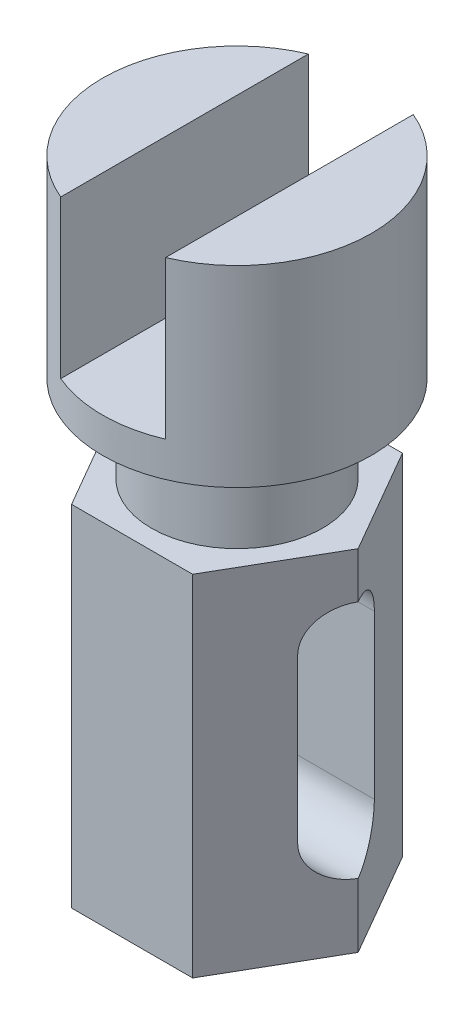
SolidWorks part; units mm, degrees
ref_plane "Front Plane" through (0, 0, 0) normal (0, 0, 1) x (1, 0, 0)
ref_plane "Top Plane" through (0, 0, 0) normal (0, 1, 0) x (1, 0, 0)
ref_plane "Right Plane" through (0, 0, 0) normal (1, 0, 0) x (0, 0, -1)
sketch "Sketch4" plane through (0, 0, 0) normal (0, 1, 0) x (1, 0, 0)
  line L1 (34.641, 0) -> (17.3205, 30)
  line L2 (17.3205, 30) -> (-17.3205, 30)
  line L3 (-17.3205, 30) -> (-34.641, 0)
  line L4 (-34.641, 0) -> (-17.3205, -30)
  line L5 (-17.3205, -30) -> (17.3205, -30)
  line L6 (17.3205, -30) -> (34.641, 0)
  circle A0 centre (0, 0) radius 30 construction
  point P1 (30, 0)
  point P10 (30, 0)
  dimension "D1" = 60
extrude "Boss-Extrude1" add sketch "Sketch4" along normal blind 100
sketch "Sketch5" plane through (0, 100, 0) normal (0, 1, 0) x (1, 0, 0)
  circle A0 centre (0, 0) radius 24.5
extrude "Boss-Extrude3" add sketch "Sketch5" along normal blind 25
ref_plane "Plane1" through (0, 125, 0) normal (0, 1, 0) x (1, 0, 0)
sketch "Sketch7" plane through (0, 125, 0) normal (0, 1, 0) x (1, 0, 0)
  circle A0 centre (0, 0) radius 38.4617
extrude "Boss-Extrude4" add sketch "Sketch7" along normal blind 55
sketch "Sketch8" plane through (0, 180, 0) normal (0, 1, 0) x (1, 0, 0)
  line L1 (-15, -39.4745) -> (15, -39.4745)
  line L2 (-15, -39.4745) -> (-15, 39.4745)
  line L3 (-15, 39.4745) -> (15, 39.4745)
  line L4 (15, -39.4745) -> (15, 39.4745)
  line L5 (-15, -39.4745) -> (15, 39.4745) construction
  line L6 (-15, 39.4745) -> (15, -39.4745) construction
  point P1 (0, 0)
  dimension "D1" = 30
extrude "Cut-Extrude1" cut sketch "Sketch8" against normal blind 45
sketch "Sketch9" plane through (0, 0, 0) normal (1, 0, 0) x (0, 0, -1)
  line L0 (0, 75.8691) -> (0, 29.2858) construction
  line L1 (0, 100) -> (0, 0) construction
  line L2 (10.9599, 75.8691) -> (10.9599, 29.2858)
  line L3 (-10.9599, 75.8691) -> (-10.9599, 29.2858)
  arc A0 (10.9599, 75.8691) -> (-10.9599, 75.8691) centre (0, 75.8691) ccw
  arc A1 (-10.9599, 29.2858) -> (10.9599, 29.2858) centre (0, 29.2858) ccw
  point P4 (0, 52.5774)
  point P9 (0, 75.8691)
  point P10 (0, 0)
extrude "Cut-Extrude2" cut sketch "Sketch9" against normal mid plane 85
